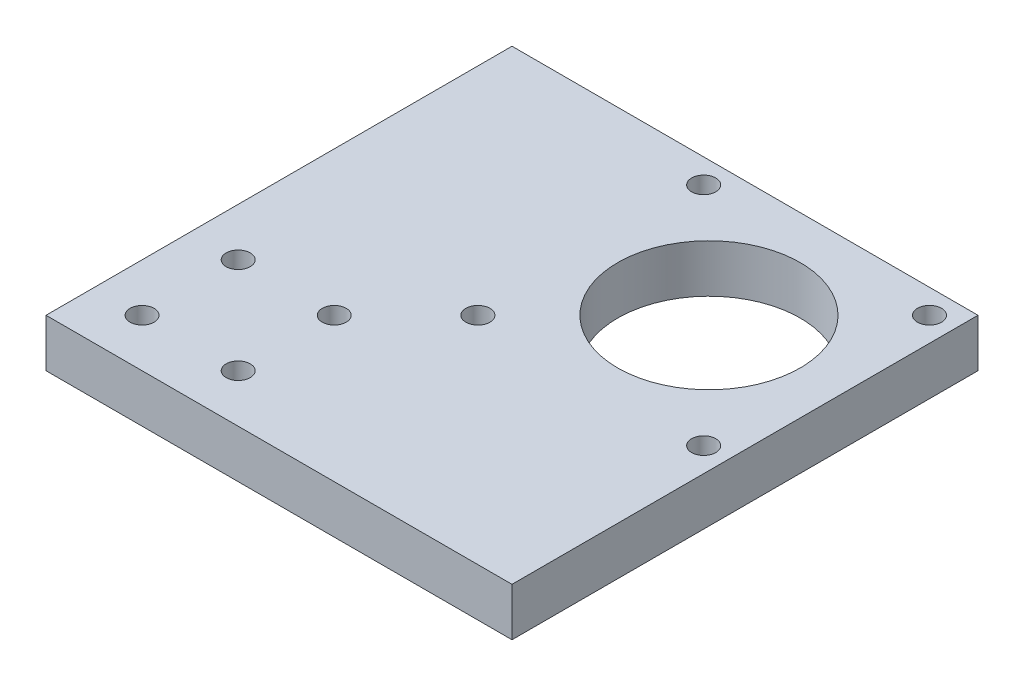
SolidWorks part; units mm, degrees
ref_plane "Front Plane" through (0, 0, 0) normal (0, 0, 1) x (1, 0, 0)
ref_plane "Top Plane" through (0, 0, 0) normal (0, 1, 0) x (1, 0, 0)
ref_plane "Right Plane" through (0, 0, 0) normal (1, 0, 0) x (0, 0, -1)
sketch "Sketch1" plane through (0, 0, 0) normal (0, 1, 0) x (1, 0, 0)
  line L0 (0, 0) -> (97, 0)
  line L1 (97, 0) -> (97, 97)
  line L2 (97, 97) -> (0, 97)
  line L3 (0, 97) -> (0, 0)
  dimension "D1" = 97
  dimension "D2" = 97
extrude "Boss-Extrude1" add sketch "Sketch1" along normal blind 10
sketch "Sketch2" plane through (0, 10, 0) normal (0, 1, 0) x (1, 0, 0)
  line L0 (97, 97) -> (0, 97) construction
  line L1 (97, 0) -> (97, 97) construction
  line L2 (0, 97) -> (0, 0) construction
  line L3 (0, 0) -> (97, 0) construction
  circle A0 centre (69, 69) radius 19
  circle A1 centre (44.95, 91.95) radius 2.51
  circle A2 centre (91.95, 91.95) radius 2.51
  circle A3 centre (91.95, 44.95) radius 2.51
  circle A4 centre (44.95, 44.95) radius 2.51
  circle A5 centre (10, 10) radius 2.5
  circle A6 centre (30, 10) radius 2.5
  circle A7 centre (30, 30) radius 2.5
  circle A8 centre (10, 30) radius 2.5
  point P22 (0, 0)
  point P23 (0, 0)
  point P24 (0, 0)
  point P25 (0, 0)
  dimension "D1" = 38
  dimension "D4" = 5.05
  dimension "D8" = 5.02
  dimension "D9" = 5
  dimension "D2" = 28
  dimension "D3" = 28
  dimension "D5" = 5.05
  dimension "D6" = 47
  dimension "D7" = 47
  dimension "D10" = 10
  dimension "D11" = 10
  dimension "D12" = 20
  dimension "D13" = 20
extrude "Cut-Extrude1" cut sketch "Sketch2" against normal blind 10
